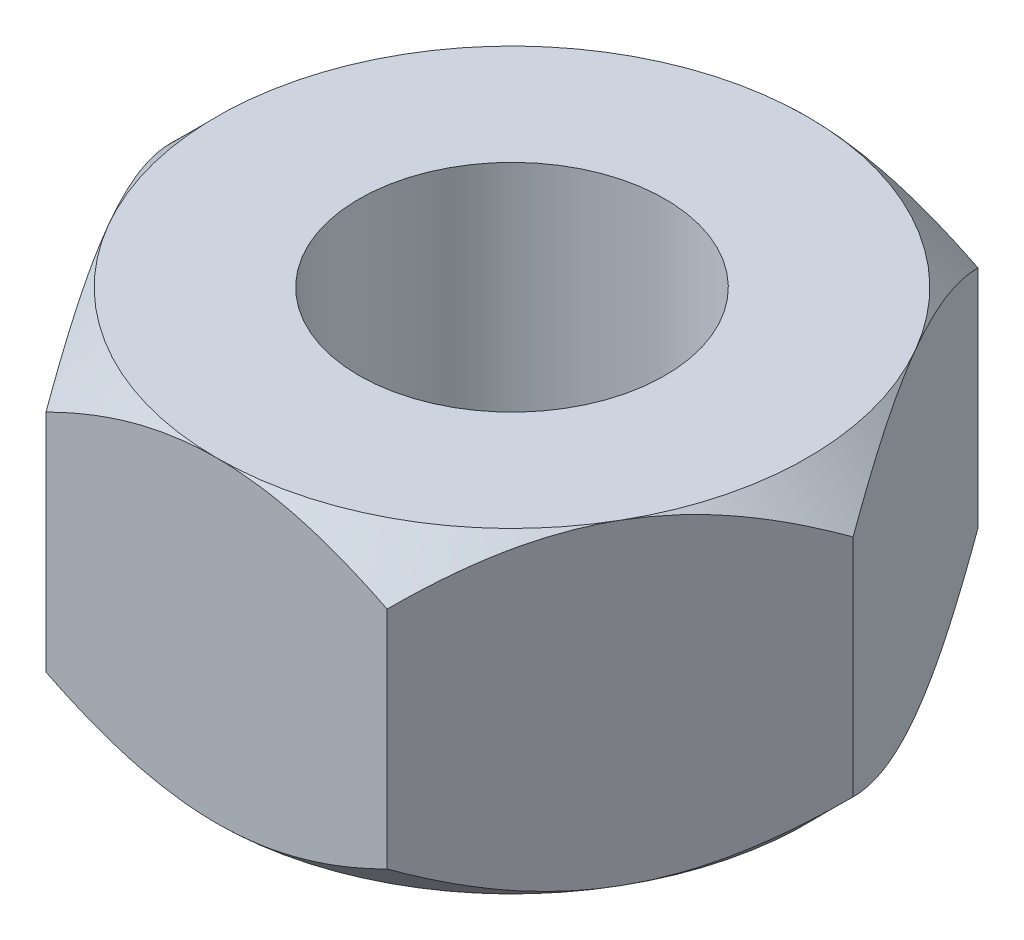
SolidWorks part; units mm, degrees
ref_plane "Front Plane" through (0, 0, 0) normal (0, 0, 1) x (1, 0, 0)
ref_plane "Top Plane" through (0, 0, 0) normal (0, 1, 0) x (1, 0, 0)
ref_plane "Right Plane" through (0, 0, 0) normal (1, 0, 0) x (0, 0, -1)
sketch "Sketch1" plane through (0, 0, 0) normal (0, 1, 0) x (1, 0, 0)
  line L1 (16.1658, 0) -> (8.0829, 14)
  line L2 (8.0829, 14) -> (-8.0829, 14)
  line L3 (-8.0829, 14) -> (-16.1658, 0)
  line L4 (-16.1658, 0) -> (-8.0829, -14)
  line L5 (-8.0829, -14) -> (8.0829, -14)
  line L6 (8.0829, -14) -> (16.1658, 0)
  circle A0 centre (0, 0) radius 14 construction
  dimension "D1" = 14
extrude "Boss-Extrude1" add sketch "Sketch1" along normal blind 15 contours L6 L1 L2 L3 L4 L5
sketch "Sketch2" plane through (0, 15, 0) normal (0, 1, 0) x (1, 0, 0)
  line L0 (-8.0829, 14) -> (-16.1658, 0) construction
  circle A0 centre (0, 0) radius 14
extrude "Cut-Extrude1" cut sketch "Sketch2" against normal blind 15 draft 45 flip side to cut
ref_plane "Plane1" through (0, 7.5, 0) normal (0, 1, 0) x (1, 0, 0)
mirror "Mirror1" about plane through (0, 7.5, 0) normal (0, 1, 0) of "Cut-Extrude1"
hole_wizard "M16x1.5 Tapped Hole1" positions "Sketch3" profile "Sketch4" tap size "M16x1.5" standard "ANSI Metric" end condition up to next
sketch "Sketch3" plane through (0, 15, 0) normal (0, 1, 0) x (1, 0, 0)
  point P0 (0, 0)
sketch "Sketch4" plane through (0, 15, 0) normal (1, 0, 0) x (0, 0, 1)
  line L0 (0, 0) -> (0, 15)
  line L1 (0, 15) -> (7.25, 15)
  line L2 (7.25, 15) -> (7.25, 0)
  line L5 (7.25, 0) -> (0, 0)
  line L11 (0, -6.35) -> (0, 107.95) construction
  dimension "Thru Tap Drill Dia." = 14.5
  dimension "Thru Tap Drill Depth" = 15
